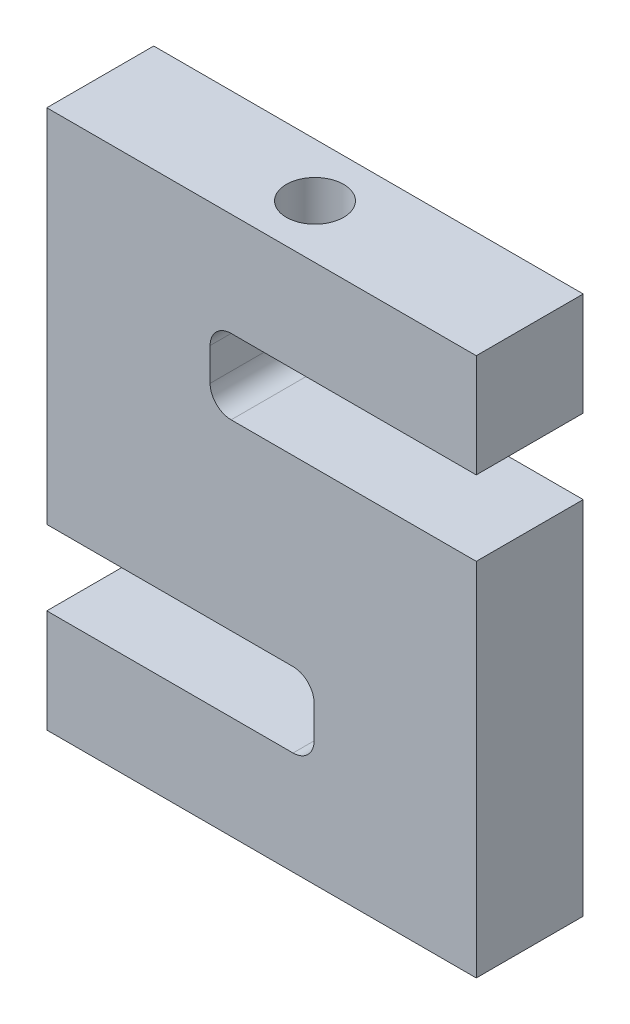
SolidWorks part; units mm, degrees
ref_plane "Front Plane" through (0, 0, 0) normal (0, 0, 1) x (1, 0, 0)
ref_plane "Top Plane" through (0, 0, 0) normal (0, 1, 0) x (1, 0, 0)
ref_plane "Right Plane" through (0, 0, 0) normal (1, 0, 0) x (0, 0, -1)
sketch "Sketch1" plane through (0, 0, 0) normal (0, 0, 1) x (1, 0, 0)
  line L12 (25.5, 32) -> (25.5, 19.739)
  line L13 (25.5, 19.739) -> (-6.1062, 19.739)
  line L14 (-6.1062, 19.739) -> (-6.1062, 10.8521)
  line L15 (-6.1062, 10.8521) -> (25.5, 10.8521)
  line L16 (25.5, 10.8521) -> (25.5, -32)
  line L17 (25.5, -32) -> (-25.5, -32)
  line L18 (-25.5, -32) -> (-25.5, -19.739)
  line L19 (-25.5, -19.739) -> (6.2424, -19.739)
  line L20 (6.2424, -19.739) -> (6.2424, -10.8521)
  line L21 (6.2424, -10.8521) -> (-25.5, -10.8521)
  line L22 (-25.5, -10.8521) -> (-25.5, 32)
  line L23 (-25.5, 32) -> (25.5, 32)
  line L24 (-25.5, 0) -> (25.5, 0) construction
  point P11 (0, 32)
  point P16 (0, 0)
  point P17 (-25.5, -8.7457)
  point P18 (-25.5, -10.8521)
  dimension "D1" = 64
  dimension "D2" = 51
  dimension "D3" = 32
extrude "Boss-Extrude1" add sketch "Sketch1" along normal blind 12.7
hole_wizard "M8x1.25 Tapped Hole1" positions "Sketch3" profile "Sketch5" tap size "M8x1.25" standard "ANSI Metric"
sketch "Sketch3" plane through (0, 32, 0) normal (0, 1, 0) x (1, 0, 0)
  point P0 (0, -6.35)
sketch "Sketch5" plane through (0, 32, 6.35) normal (1, 0, 0) x (0, 0, 1)
  line L0 (0, 0) -> (0, 11.1909)
  line L1 (0, 11.1909) -> (3.4, 9.1479)
  line L2 (3.4, 9.1479) -> (3.4, 0)
  line L5 (3.4, 0) -> (0, 0)
  line L10 (0, 11.1909) -> (-3.4, 9.1479) construction
  line L11 (0, -6.35) -> (0, 107.95) construction
  dimension "Tap Drill Dia." = 6.8
  dimension "Tap Drill Depth" = 9.1479
  dimension "Drill Angle" = 118
cosmetic thread "Hole Thread1" parameters "D1"=8.6122, "D2"=8
hole_wizard "M8x1.25 Tapped Hole2" positions "Sketch6" profile "Sketch7" tap size "M8x1.25" standard "ANSI Metric"
sketch "Sketch6" plane through (0, -32, 0) normal (0, -1, 0) x (-1, 0, 0)
  point P0 (0, -6.35)
sketch "Sketch7" plane through (0, -32, 6.35) normal (1, 0, 0) x (0, 0, -1)
  line L0 (0, 0) -> (0, 11.1909)
  line L1 (0, 11.1909) -> (3.4, 9.1479)
  line L2 (3.4, 9.1479) -> (3.4, 0)
  line L5 (3.4, 0) -> (0, 0)
  line L10 (0, 11.1909) -> (-3.4, 9.1479) construction
  line L11 (0, -6.35) -> (0, 107.95) construction
  dimension "Tap Drill Dia." = 6.8
  dimension "Tap Drill Depth" = 9.1479
  dimension "Drill Angle" = 118
cosmetic thread "Hole Thread2" parameters "D1"=8.6122, "D2"=8
fillet "Fillet3" radius 2.5 1 edges at (-6.1062, 19.739, 6.35)
fillet "Fillet5" radius 2.5 1 edges at (-6.1062, 10.8521, 6.35)
fillet "Fillet6" radius 2.5 1 edges at (6.2424, -10.8521, 6.35)
fillet "Fillet7" radius 2.5 1 edges at (6.2424, -19.739, 6.35)
